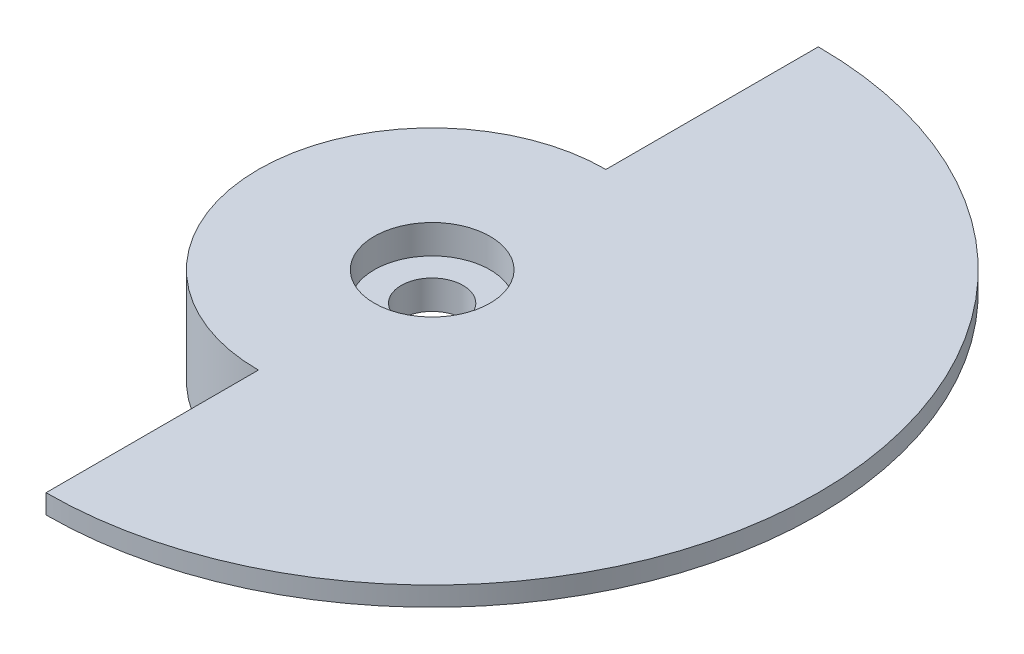
SolidWorks part; units mm, degrees
ref_plane "Front Plane" through (0, 0, 0) normal (0, 0, 1) x (1, 0, 0)
ref_plane "Top Plane" through (0, 0, 0) normal (0, 1, 0) x (1, 0, 0)
ref_plane "Right Plane" through (0, 0, 0) normal (1, 0, 0) x (0, 0, -1)
other "Configuration Table"
sketch "草图1" plane through (0, 0, 0) normal (0, 1, 0) x (1, 0, 0)
  circle A0 centre (0, 0) radius 7.5
  circle A1 centre (0, 0) radius 9
extrude "凸台-拉伸1" add sketch "草图1" along normal blind 6
sketch "草图2" plane through (0, 6, 0) normal (0, 1, 0) x (1, 0, 0)
  line L0 (0, 9) -> (0, 20)
  line L1 (0, -9) -> (0, -20)
  circle A0 centre (0, 0) radius 20
  circle A1 centre (0, 0) radius 9 construction
  circle A2 centre (0, 0) radius 9
  circle M3 centre (0, 0) radius 9
extrude "凸台-拉伸2" add sketch "草图2" against normal blind 1 contours L1 A0 L0 M3
sketch "草图4" plane through (0, 0, 0) normal (0, -1, 0) x (1, 0, 0)
  line L0 (0.9566, 6.3261) -> (0.8566, 6.3261) construction
  line L1 (0.9496, 7.3388) -> (0.9635, 5.3133) construction
  line L2 (-1.0434, 6.3123) -> (-0.9434, 6.3123) construction
  line L3 (-1.0364, 5.2996) -> (-1.0504, 7.3251) construction
  line L4 (0.8566, 6.3261) -> (0.8566, 7.4509)
  line L5 (0.8566, 6.3261) -> (0.8566, 5.4329)
  line L6 (-0.9434, 6.3123) -> (-0.9434, 7.4404)
  line L7 (-0.9434, 6.3123) -> (-0.9434, 5.4185)
  line L8 (6.3123, 0.9434) -> (5.4185, 0.9434)
  line L9 (6.3123, 0.9434) -> (7.4404, 0.9434)
  line L10 (6.3261, -0.8566) -> (7.4509, -0.8566)
  line L11 (6.3261, -0.8566) -> (5.4329, -0.8566)
  line L12 (0.9434, -6.3123) -> (0.9434, -5.4185)
  line L13 (0.9434, -6.3123) -> (0.9434, -7.4404)
  line L14 (-0.8566, -6.3261) -> (-0.8566, -7.4509)
  line L15 (-0.8566, -6.3261) -> (-0.8566, -5.4329)
  line L16 (-6.3123, -0.9434) -> (-5.4185, -0.9434)
  line L17 (-6.3123, -0.9434) -> (-7.4404, -0.9434)
  line L18 (-6.3261, 0.8566) -> (-7.4509, 0.8566)
  line L19 (-6.3261, 0.8566) -> (-5.4329, 0.8566)
  arc A0 (0.8566, 7.4509) -> (-0.9434, 7.4404) centre (0, 0) ccw
  arc A1 (0.8566, 5.4329) -> (-0.9434, 5.4185) centre (0, 0) ccw
  arc A2 (5.4329, -0.8566) -> (5.4185, 0.9434) centre (0, 0) ccw
  arc A3 (7.4509, -0.8566) -> (7.4404, 0.9434) centre (0, 0) ccw
  arc A4 (-0.8566, -5.4329) -> (0.9434, -5.4185) centre (0, 0) ccw
  arc A5 (-0.8566, -7.4509) -> (0.9434, -7.4404) centre (0, 0) ccw
  arc A6 (-5.4329, 0.8566) -> (-5.4185, -0.9434) centre (0, 0) ccw
  arc A7 (-7.4509, 0.8566) -> (-7.4404, -0.9434) centre (0, 0) ccw
  point P35 (0, 0)
  dimension "D1" = 4
extrude "凸台-拉伸3" add sketch "草图4" against normal blind 3
sketch "草图5" plane through (0, 6, 0) normal (0, 1, 0) x (1, 0, 0)
  circle A0 centre (0, 0) radius 7.5
extrude "凸台-拉伸4" add sketch "草图5" against normal blind 3
sketch "草图6" plane through (0, 6, 0) normal (0, 1, 0) x (1, 0, 0)
  circle A0 centre (0, 0) radius 1.6
extrude "切除-拉伸1" cut sketch "草图6" against normal blind 3
sketch "草图7" plane through (0, 6, 0) normal (0, 1, 0) x (1, 0, 0)
  circle A0 centre (0, 0) radius 3
extrude "切除-拉伸2" cut sketch "草图7" against normal blind 1.5
chamfer "倒角1" distance 1 angle 45 1 edges at (0, 0, 9)
